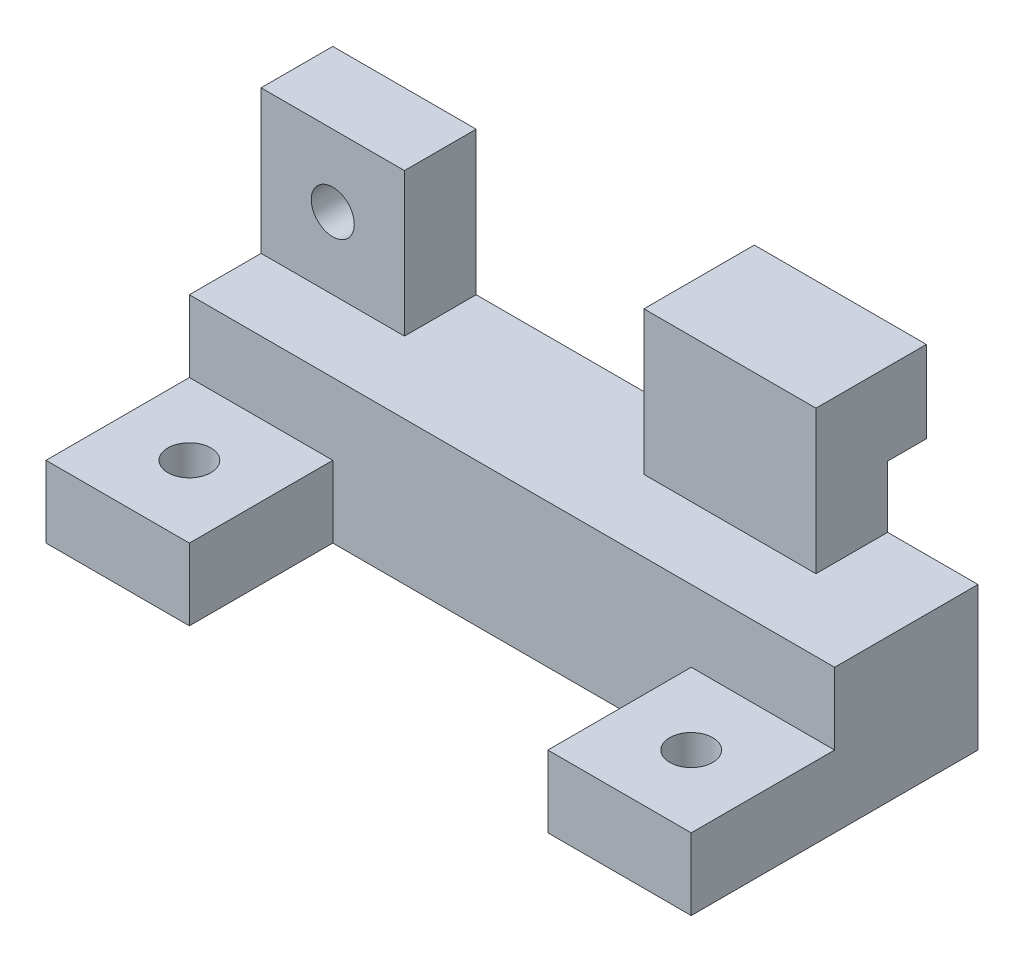
SolidWorks part; units mm, degrees
ref_plane "Front Plane" through (0, 0, 0) normal (0, 0, 1) x (1, 0, 0)
ref_plane "Top Plane" through (0, 0, 0) normal (0, 1, 0) x (1, 0, 0)
ref_plane "Right Plane" through (0, 0, 0) normal (1, 0, 0) x (0, 0, -1)
sketch "Sketch1" plane through (0, 0, 0) normal (0, 0, 1) x (1, 0, 0)
  line L1 (0, 0) -> (45, 0)
  line L2 (0, 0) -> (0, 10)
  line L3 (0, 10) -> (45, 10)
  line L4 (45, 0) -> (45, 10)
  dimension "D1" = 45
  dimension "D2" = 10
extrude "Boss-Extrude1" add sketch "Sketch1" along normal blind 10
sketch "Sketch2" plane through (0, 10, 0) normal (0, 1, 0) x (1, 0, 0)
  line L0 (45, 0) -> (0, 0) construction
  line L1 (45, 0) -> (35, 0)
  line L2 (45, 0) -> (45, -5)
  line L3 (45, -5) -> (35, -5)
  line L4 (35, 0) -> (35, -5)
  line L5 (6.3, 0) -> (18.3, 0)
  line L6 (6.3, 0) -> (6.3, -5)
  line L7 (6.3, -5) -> (18.3, -5)
  line L8 (18.3, 0) -> (18.3, -5)
  line L9 (0, -10) -> (0, 0) construction
  dimension "D1" = 5
  dimension "D2" = 10
  dimension "D3" = 5
  dimension "D4" = 6.3
  dimension "D5" = 12
extrude "Boss-Extrude2" add sketch "Sketch2" along normal blind 10
sketch "Sketch3" plane through (0, 0, 10) normal (0, 0, 1) x (1, 0, 0)
  line L1 (0, 0) -> (10, 0)
  line L2 (0, 0) -> (0, 5)
  line L3 (0, 5) -> (10, 5)
  line L4 (10, 0) -> (10, 5)
  line L5 (45, 0) -> (35, 0)
  line L6 (45, 0) -> (45, 5)
  line L7 (45, 5) -> (35, 5)
  line L8 (35, 0) -> (35, 5)
  point P10 (0, 0)
  dimension "D1" = 10
  dimension "D2" = 10
  dimension "D3" = 5
  dimension "D4" = 5
extrude "Boss-Extrude3" add sketch "Sketch3" along normal blind 10
sketch "Sketch4" plane through (0, 0, 0) normal (-1, 0, 0) x (0, 0, 1)
  line L0 (0, 10) -> (0, 0) construction
  line L1 (20, 0) -> (0, 0) construction
  circle A0 centre (5, 5) radius 1.5
  dimension "D3" = 3
  dimension "D1" = 5
  dimension "D2" = 5
extrude "Cut-Extrude1" cut sketch "Sketch4" against normal blind 5
sketch "Sketch7" plane through (45, 0, 0) normal (1, 0, 0) x (0, 0, -1)
  line L3 (-10, 10) -> (0, 10)
  line L4 (-10, 10) -> (-10, 0)
  line L5 (-10, 0) -> (0, 0)
  line L6 (0, 10) -> (0, 0)
sketch "Sketch9" plane through (0, 5, 0) normal (0, 1, 0) x (1, 0, 0)
  line L0 (45, -20) -> (45, -10) construction
  line L1 (45, -20) -> (35, -20) construction
  circle A0 centre (40, -15) radius 1.5
  dimension "D3" = 3
  dimension "D1" = 5
  dimension "D2" = 5
extrude "Cut-Extrude6" cut sketch "Sketch9" against normal blind 5
sketch "Sketch10" plane through (0, 0, 5) normal (0, 0, 1) x (1, 0, 0)
  line L0 (35, 20) -> (35, 10) construction
  line L3 (35, 10) -> (45, 10) construction
  circle A0 centre (40, 15) radius 1.5
  dimension "D3" = 3
  dimension "D1" = 5
  dimension "D2" = 5
extrude "Cut-Extrude7" cut sketch "Sketch10" against normal blind 5
sketch "Sketch11" plane through (0, 0, 0) normal (0, 0, -1) x (-1, 0, 0)
  line L0 (-18.3, 20) -> (-18.3, 10) construction
  line L1 (-6.3, 20) -> (-18.3, 20)
  line L2 (-6.3, 20) -> (-6.3, 14.3)
  line L3 (-6.3, 14.3) -> (-18.3, 14.3)
  line L4 (-18.3, 20) -> (-18.3, 14.3)
  line L5 (-18.3, 14.3) -> (-6.3, 14.3) construction
extrude "Boss-Extrude4" add sketch "Sketch11" along normal blind 2.7
extrude "Boss-Extrude5" add sketch "Sketch7" along normal blind 35
sketch "Sketch13" plane through (0, 10, 0) normal (0, 1, 0) x (1, 0, 0)
  line L0 (80, 0) -> (45, 0) construction
  line L1 (61.7, 0) -> (73.7, 0)
  line L2 (61.7, 0) -> (61.7, -5)
  line L3 (61.7, -5) -> (73.7, -5)
  line L4 (73.7, 0) -> (73.7, -5)
  line L5 (80, 0) -> (80, -10) construction
  dimension "D1" = 6.3
  dimension "D2" = 5
  dimension "D3" = 12
extrude "Boss-Extrude6" add sketch "Sketch13" along normal blind 10
sketch "Sketch14" plane through (0, 0, 0) normal (0, 0, -1) x (-1, 0, 0)
  line L0 (-61.7, 20) -> (-61.7, 10) construction
  line L1 (-73.7, 20) -> (-61.7, 20)
  line L2 (-73.7, 20) -> (-73.7, 14.3)
  line L3 (-73.7, 14.3) -> (-61.7, 14.3)
  line L4 (-61.7, 20) -> (-61.7, 14.3)
  dimension "D1" = 5.7
extrude "Boss-Extrude7" add sketch "Sketch14" along normal blind 2.7
sketch "Sketch15" plane through (35, 0, 0) normal (-1, 0, 0) x (0, 0, 1)
  line L1 (0, 20) -> (20, 20)
  line L2 (0, 20) -> (0, 0)
  line L3 (0, 0) -> (20, 0)
  line L4 (20, 20) -> (20, 0)
  line L5 (0, 20) -> (-5, 20)
  line L6 (0, 20) -> (0, 0)
  line L7 (0, 0) -> (-5, 0)
  line L8 (-5, 20) -> (-5, 0)
  line M1 (0, 10) -> (5, 10)
  line M2 (5, 10) -> (5, 20)
  line M3 (5, 20) -> (0, 20)
  line M4 (0, 20) -> (0, 10)
  dimension "D1" = 5
extrude "Cut-Extrude9" cut sketch "Sketch15" along normal blind 50 contours L4 L1 L2 L3 M2 M1 | M4 M1 M2 M3 | L5 L8 L7 L2 M4
sketch "Sketch16" plane through (0, 0, 10) normal (0, 0, 1) x (1, 0, 0)
  line L1 (80, 0) -> (70, 0)
  line L2 (80, 0) -> (80, 5)
  line L3 (80, 5) -> (70, 5)
  line L4 (70, 0) -> (70, 5)
  dimension "D1" = 5
  dimension "D2" = 10
extrude "Boss-Extrude8" add sketch "Sketch16" along normal blind 10
sketch "Sketch17" plane through (0, 5, 0) normal (0, 1, 0) x (1, 0, 0)
  line L0 (80, -20) -> (80, -10) construction
  line L1 (80, -20) -> (70, -20) construction
  circle A0 centre (75, -15) radius 1.5
  dimension "D3" = 3
  dimension "D1" = 5
  dimension "D2" = 5
extrude "Cut-Extrude10" cut sketch "Sketch17" against normal blind 5
